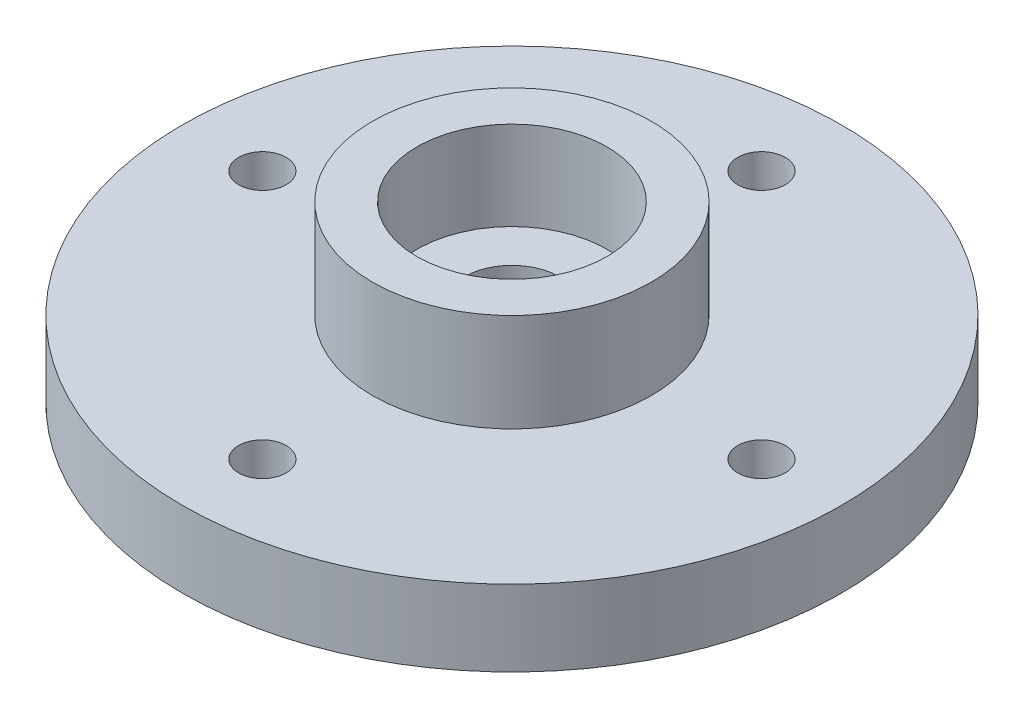
SolidWorks part; units mm, degrees
ref_plane "Alzado" through (0, 0, 0) normal (0, 0, 1) x (1, 0, 0)
ref_plane "Planta" through (0, 0, 0) normal (0, 1, 0) x (1, 0, 0)
ref_plane "Vista lateral" through (0, 0, 0) normal (1, 0, 0) x (0, 0, -1)
sketch "Croquis1" plane through (0, 0, 0) normal (0, 1, 0) x (1, 0, 0)
  circle A0 centre (0, 0) radius 10.4
  dimension "D1" = 20.8
extrude "Saliente-Extruir1" add sketch "Croquis1" along normal blind 2.4
sketch "Croquis2" plane through (0, 2.4, 0) normal (0, 1, 0) x (1, 0, 0)
  circle A0 centre (0, 0) radius 4.4
  dimension "D1" = 8.8
extrude "Saliente-Extruir2" add sketch "Croquis2" along normal blind 5.5 from surface at -2.4 starting at face at (0, 0, 10.4)
sketch "Croquis3" plane through (0, 5.5, 0) normal (0, 1, 0) x (1, 0, 0)
  circle A0 centre (0, 0) radius 3
  dimension "D1" = 6
extrude "Cortar-Extruir1" cut sketch "Croquis3" against normal blind 2.8
sketch "Croquis4" plane through (0, 2.4, 0) normal (0, 1, 0) x (1, 0, 0)
  line L0 (0, 13.0611) -> (0, -13.0611) construction
  circle A0 centre (0, 7.875) radius 0.75
  circle A1 centre (7.875, 0) radius 0.75
  circle A2 centre (0, -7.875) radius 0.75
  circle A3 centre (-7.875, 0) radius 0.75
  point P3 (0, 0)
  point P15 (0, 0)
  dimension "D1" = 7.875
  dimension "D2" = 1.5
  dimension "D3" = 4
extrude "Cortar-Extruir2" cut sketch "Croquis4" against normal through all
sketch "Croquis5" plane through (0, 2.7, 0) normal (0, 1, 0) x (1, 0, 0)
  circle A0 centre (0, 0) radius 1.5
  dimension "D1" = 3
extrude "Cortar-Extruir3" cut sketch "Croquis5" against normal through all
